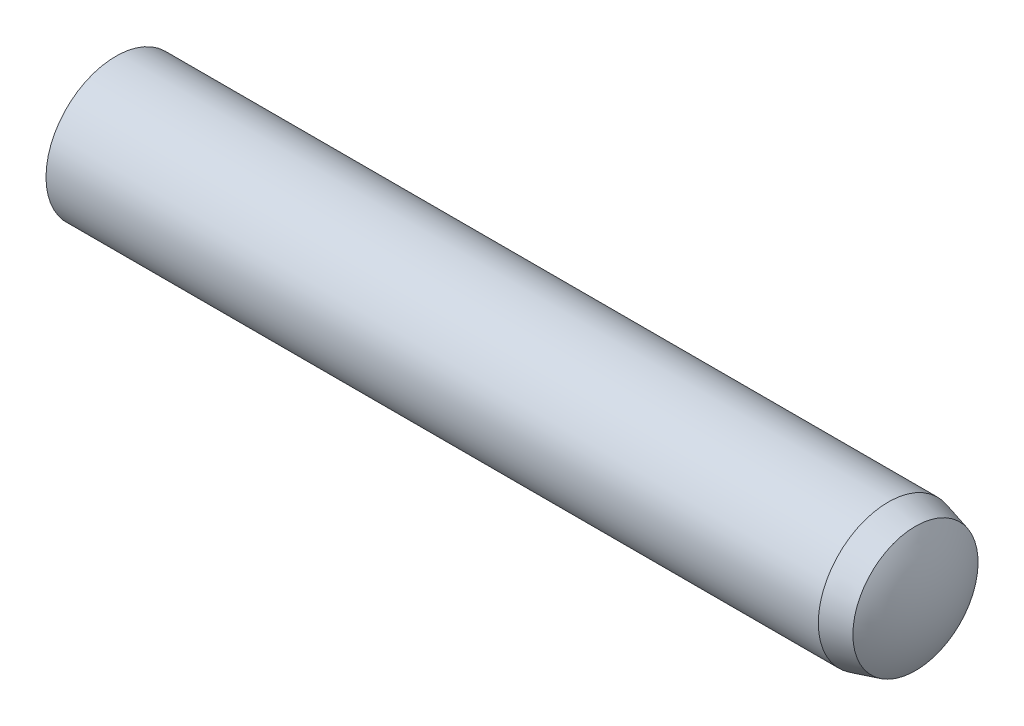
SolidWorks part; units mm, degrees
material "Cast Alloy Steel"
ref_plane "Front Plane" through (0, 0, 0) normal (0, 0, 1) x (1, 0, 0)
ref_plane "Top Plane" through (0, 0, 0) normal (0, 1, 0) x (1, 0, 0)
ref_plane "Right Plane" through (0, 0, 0) normal (1, 0, 0) x (0, 0, -1)
sketch "Sketch1" plane through (0, 0, 0) normal (0, 0, 1) x (1, 0, 0)
  line L0 (-6, 0) -> (6, 0) construction
  line L1 (6, 1) -> (6, -1) construction
  line L2 (-6, 1) -> (-6, -1) construction
  line L3 (5.35, 1) -> (5.35, -1) construction
  line L4 (-5.7, 1) -> (-5.7, -1) construction
  line L5 (-6, 0) -> (-5.7, 0) construction
  line L6 (6, 0) -> (5.35, 0) construction
  line L7 (5.74, 1) -> (5.74, -1) construction
  dimension "Dia" = 2
  dimension "Length" = 12
  dimension "D1" = 0.65
  dimension "D2" = 0.3
  dimension "D3" = 0.39
sketch "Sketch2" plane through (0, 0, 0) normal (1, 0, 0) x (0, 0, -1)
  circle A0 centre (0, 0) radius 1
extrude "Extrude1" add sketch "Sketch2" against normal up to vertex (6 mm away) and the other way up to vertex (6 mm away) up to point (-6, 0, 0) other way up to point (6, 0, 0)
sketch "Sketch5" plane through (0, 0, 0) normal (0, 0, 1) x (1, 0, 0)
  line L0 (5.35, 1) -> (5.35, 1.5)
  line L1 (5.35, 1.5) -> (6.5, 1.5)
  line L2 (6.5, 1.5) -> (6.5, 0)
  line L3 (6, 0) -> (6.5, 0)
  line L5 (-5.7, 1) -> (-5.7, 1.5)
  line L6 (-5.7, 1.5) -> (-6.5, 1.5)
  line L7 (-6.5, 1.5) -> (-6.5, 0)
  line L8 (5.35, 1) -> (5.74, 0.8955)
  line L10 (-6, 0) -> (-6.5, 0)
  line L11 (-6, 1) -> (-6, -1) construction
  line L13 (5.35, 1) -> (5.35, -1) construction
  line L15 (-6, 0) -> (6, 0) construction
  line L16 (5.74, 1) -> (5.74, -1) construction
  line L17 (6, 1) -> (6, -1) construction
  arc A0 (5.74, 0.8955) -> (6, 0) centre (4.3278, 0) cw
  arc A1 (-5.7, 1) -> (-6, 0) centre (-4.1833, 0) ccw
  dimension "D1" = 15
  dimension "D2" = 0.5
revolve "Cut-Revolve1" cut sketch "Sketch5" angle 360 about L0
equation "\"D1@Sketch1\" = \"Dia@Sketch1\"*.325"
equation "\"D2@Sketch1\" = \"Dia@Sketch1\"*.15"
equation "\"D3@Sketch1\" = \"D1@Sketch1\"*.6"
